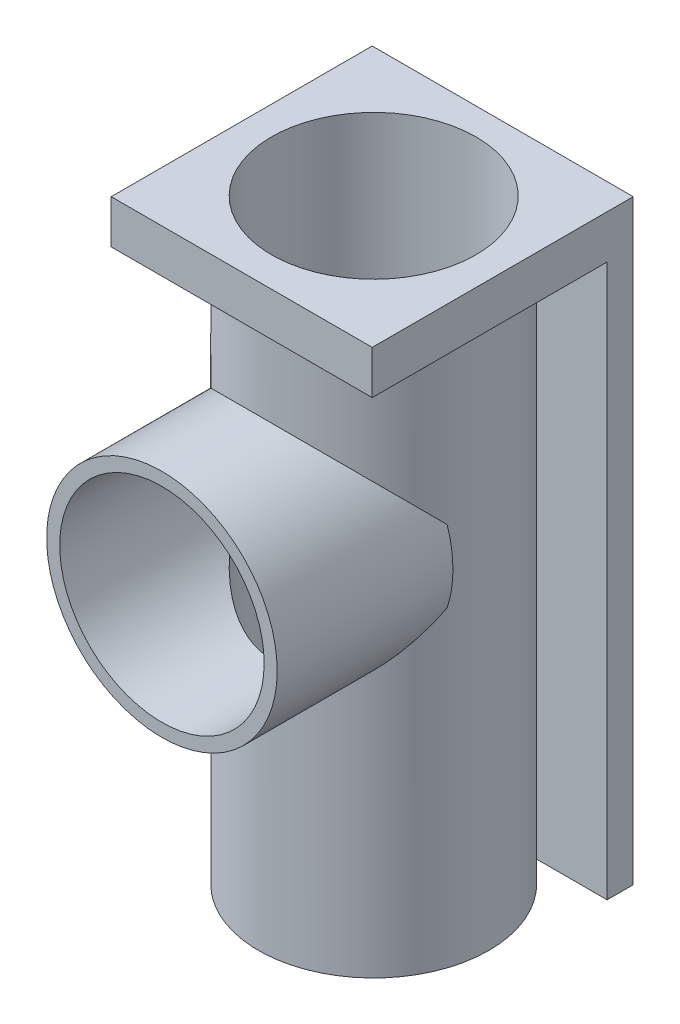
SolidWorks part; units mm, degrees
ref_plane "Front Plane" through (0, 0, 0) normal (0, 0, 1) x (1, 0, 0)
ref_plane "Top Plane" through (0, 0, 0) normal (0, 1, 0) x (1, 0, 0)
ref_plane "Right Plane" through (0, 0, 0) normal (1, 0, 0) x (0, 0, -1)
ref_plane "Plane1" through (0, 47, 0) normal (0, -1, 0) x (1, 0, 0)
sketch "Sketch1" plane through (0, 47, 0) normal (0, -1, 0) x (1, 0, 0)
  line L0 (-30, -78.3454) -> (30, -78.3454)
  line L1 (30, -78.3454) -> (30, -18.3454)
  line L2 (30, -18.3454) -> (-30, -18.3454)
  line L3 (-30, -18.3454) -> (-30, -78.3454)
extrude "Boss-Extrude1" add sketch "Sketch1" against normal blind 10
sketch "Sketch2" plane through (0, 47, 0) normal (0, -1, 0) x (1, 0, 0)
  line L0 (11.9395, -72.3454) -> (30, -72.3454)
  line L1 (30, -72.3454) -> (30, -78.3454)
  line L2 (30, -78.3454) -> (-30, -78.3454)
  line L3 (-30, -78.3454) -> (-30, -72.3454)
  line L4 (-30, -72.3454) -> (-11.9395, -72.3454)
  arc A0 (-11.9395, -72.3454) -> (11.9395, -72.3454) centre (0, -48.6874) cw
extrude "Boss-Extrude2" add sketch "Sketch2" along normal blind 127
ref_plane "Plane2" through (0, 54, 0) normal (0, 1, 0) x (1, 0, 0)
sketch "Sketch3" plane through (0, 54, 0) normal (0, 1, 0) x (1, 0, 0)
  line L0 (27, 75.3454) -> (-27, 75.3454)
  line L1 (-27, 75.3454) -> (-27, 21.3454)
  line L2 (-27, 21.3454) -> (27, 21.3454)
  line L3 (27, 21.3454) -> (27, 75.3454)
extrude "Cut-Extrude1" cut sketch "Sketch3" against normal blind 4
ref_plane "Plane3" through (0, 0, -48.6874) normal (0, 0, -1) x (-1, 0, 0)
sketch "Sketch4" plane through (0, 0, -48.6874) normal (0, 0, -1) x (-1, 0, 0)
  line L0 (-26.5, 50) -> (0, 50)
  line L1 (0, 50) -> (0, 54)
  line L2 (0, 54) -> (-26.5, 54)
  line L3 (-26.5, 54) -> (-26.5, 50)
  line L4 (0, 50) -> (0, 54) construction
revolve "Revolve1" add sketch "Sketch4" angle 360 about L4
sketch "Sketch5" plane through (0, 0, 0) normal (0, 1, 0) x (1, 0, 0)
  line L0 (0, 0) -> (26.5, 0)
  line L1 (26.5, 0) -> (26.5, 40.4)
  line L2 (26.5, 40.4) -> (0, 40.4)
  line L3 (0, 40.4) -> (0, 0)
  line L4 (0, 40.4) -> (0, 0) construction
revolve "Revolve2" add sketch "Sketch5" angle 360 about L4
hole_wizard "M42 Clearance Hole1" positions "Sketch7" profile "Sketch6" hole size "M42" standard "ANSI Metric"
sketch "Sketch7" plane through (0, 0, 0) normal (0, 0, 1) x (1, 0, 0)
  point P0 (0, 0)
sketch "Sketch6" plane through (0, 0, 0) normal (1, 0, 0) x (0, -1, 0)
  line L0 (0, 0) -> (0, 40.8)
  line L1 (0, 40.8) -> (23.5, 40.8)
  line L2 (23.5, 40.8) -> (23.5, 0)
  line L5 (23.5, 0) -> (0, 0)
  line L10 (0, 40.8) -> (-23.5, 40.8) construction
  line L11 (0, -6.35) -> (0, 107.95) construction
  dimension "Hole Dia." = 47
  dimension "Hole Depth" = 40.8
  dimension "Drill Angle" = 180
hole_wizard "M42 Clearance Hole2" positions "Sketch9" profile "Sketch8" hole size "M42" standard "ANSI Metric"
sketch "Sketch9" plane through (0, -80, 0) normal (0, -1, 0) x (-1, 0, 0)
  point P0 (0, 48.6874)
sketch "Sketch8" plane through (0, -80, -48.6874) normal (1, 0, 0) x (0, 0, -1)
  line L0 (0, 0) -> (0, 137)
  line L1 (0, 137) -> (23.5, 137)
  line L2 (23.5, 137) -> (23.5, 0)
  line L5 (23.5, 0) -> (0, 0)
  line L11 (0, -6.35) -> (0, 107.95) construction
  dimension "Thru Hole Dia." = 47
  dimension "Thru Hole Depth" = 137
